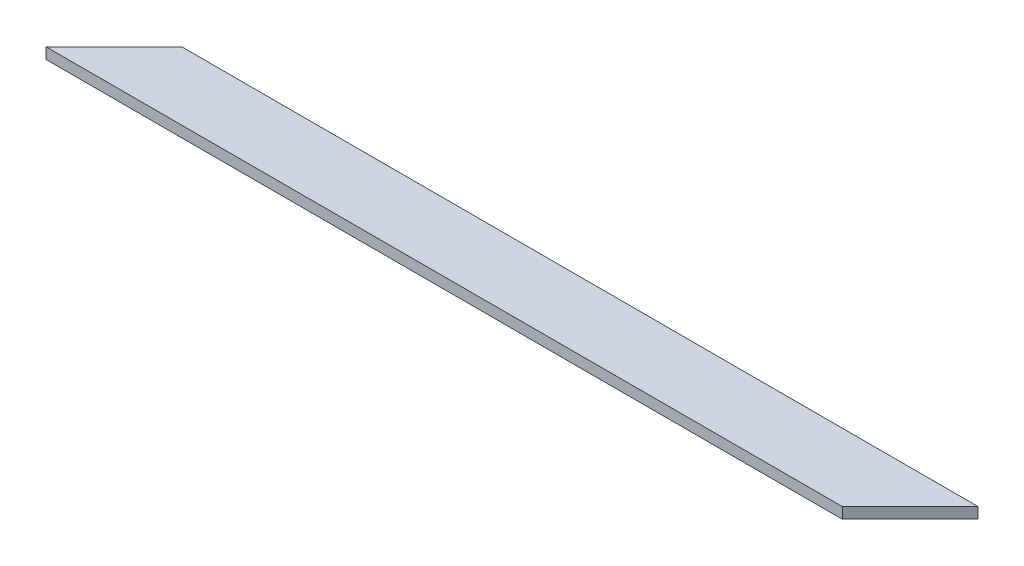
SolidWorks part; units mm, degrees
material "PE High Density"
ref_plane "Front Plane" through (0, 0, 0) normal (0, 0, 1) x (1, 0, 0)
ref_plane "Top Plane" through (0, 0, 0) normal (0, 1, 0) x (1, 0, 0)
ref_plane "Right Plane" through (0, 0, 0) normal (1, 0, 0) x (0, 0, -1)
sketch "Sketch2" plane through (0, 0, 0) normal (0, 1, 0) x (1, 0, 0)
  line L0 (-6617.4938, 2309.8125) -> (-6617.4938, 2176.4625) construction
  line L1 (-6617.4938, 2309.8125) -> (-5052.8538, 2309.8125)
  line L3 (-6750.8438, 2176.4625) -> (-5186.2038, 2176.4625)
  line L5 (-5052.8538, 2309.8125) -> (-5186.2038, 2309.8125) construction
  line L6 (-6750.8438, 2176.4625) -> (-6617.4938, 2309.8125)
  line L7 (-5186.2038, 2309.8125) -> (-5186.2038, 2176.4625) construction
  line L8 (-5052.8538, 2309.8125) -> (-5186.2038, 2176.4625)
  dimension "D1" = 133.35
  dimension "D2" = 1697.99
  dimension "D3" = 133.35
  dimension "D4" = 133.35
  dimension "D5" = 1431.29
extrude "Boss-Extrude1" add sketch "Sketch2" along normal blind 21.59 contours L3 L8 L1 L6
